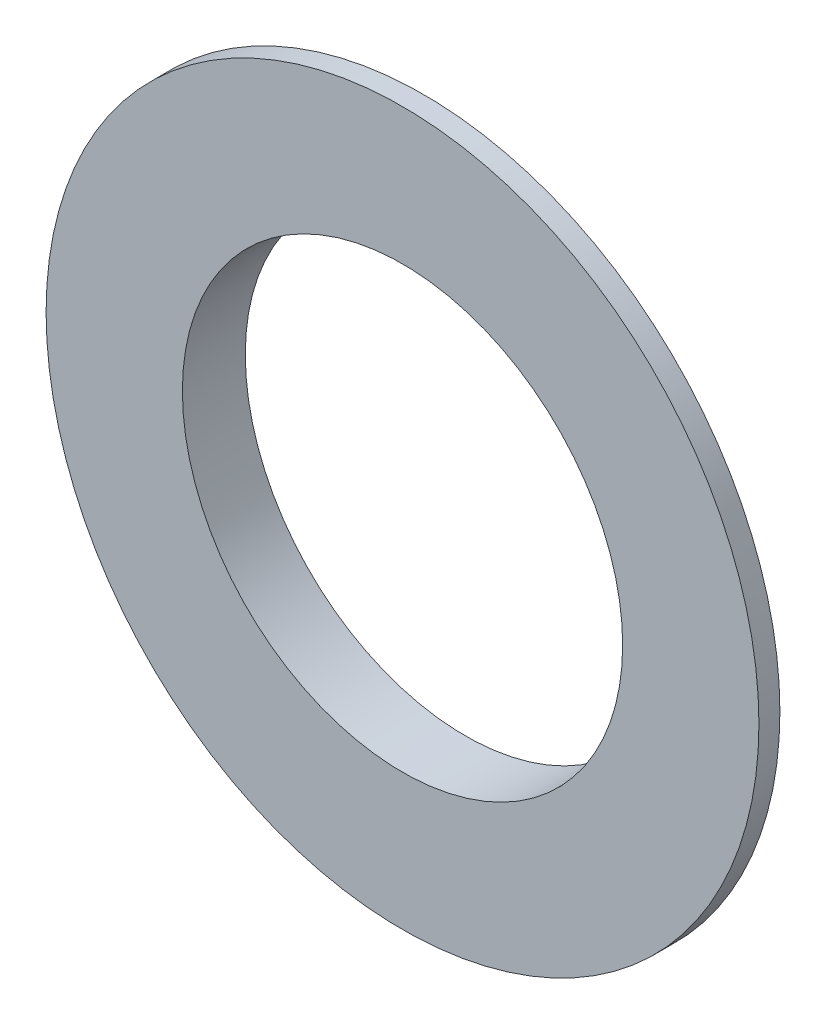
SolidWorks part; units mm, degrees
ref_plane "Front Plane" through (0, 0, 0) normal (0, 0, 1) x (1, 0, 0)
ref_plane "Top Plane" through (0, 0, 0) normal (0, 1, 0) x (1, 0, 0)
ref_plane "Right Plane" through (0, 0, 0) normal (1, 0, 0) x (0, 0, -1)
sketch "Sketch2" plane through (0, 0, 0) normal (0, 1, 0) x (1, 0, 0)
  line L0 (10.5, 0) -> (10.5, 3)
  line L1 (10.5, 3) -> (17, 1)
  line L2 (17, 1) -> (17, 0)
  line L3 (17, 0) -> (10.5, 0)
  line L4 (0, 0) -> (0, 8.028) construction
  dimension "D1" = 3
  dimension "D2" = 1
  dimension "D3" = 10.5
  dimension "D4" = 17
revolve "Revolve1" add sketch "Sketch2" angle 360 about L4
